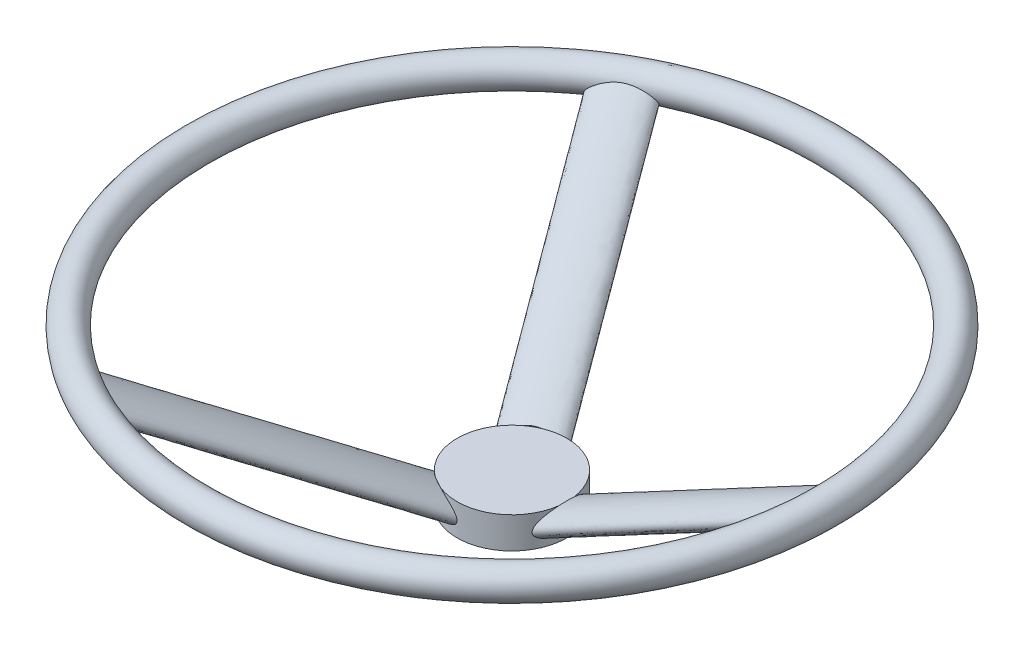
SolidWorks part; units mm, degrees
ref_plane "Front Plane" through (0, 0, 0) normal (0, 0, 1) x (1, 0, 0)
ref_plane "Top Plane" through (0, 0, 0) normal (0, 1, 0) x (1, 0, 0)
ref_plane "Right Plane" through (0, 0, 0) normal (1, 0, 0) x (0, 0, -1)
sketch "Sketch1" plane through (0, 0, 0) normal (0, 0, 1) x (1, 0, 0)
  line L1 (0, 0) -> (35, 0)
  line L2 (0, 0) -> (0, 20)
  line L3 (0, 20) -> (35, 20)
  line L4 (35, 0) -> (35, 20)
  circle A0 centre (200, 100) radius 10
  dimension "D3" = 20
  dimension "D1" = 35
  dimension "D2" = 20
  dimension "D4" = 100
  dimension "D5" = 200
revolve "Revolve1" add sketch "Sketch1" angle 360 about L2
sketch "Sketch3" plane through (0, 0, 0) normal (0, 0, 1) x (1, 0, 0)
  line L0 (200, 100) -> (35, 12)
  line L1 (35, 0) -> (35, 20) construction
  arc A0 (200, 90) -> (200, 110) centre (200, 100) ccw construction
  dimension "D1" = 8
ref_plane "Plane1" through (200, 100, 0) normal (0.8824, 0.4706, 0) x (0, 0, -1)
sketch "Sketch4" plane through (200, 100, 0) normal (0.8824, 0.4706, 0) x (0, 0, -1)
  ellipse E0 centre (0, 0.0063) end of major axis (17.5, 0.0063) minor radius 7.5
  point P1 (0, 0)
  point P7 (0, 0)
  dimension "D1" = 35
  dimension "D2" = 15
extrude "Boss-Extrude1" add sketch "Sketch4" against normal up to surface (192.3109 mm away)
pattern_circular "CirPattern1" count 3 over 360 about axis through (0, 20, 0) along (0, -1, 0) of "Boss-Extrude1"
